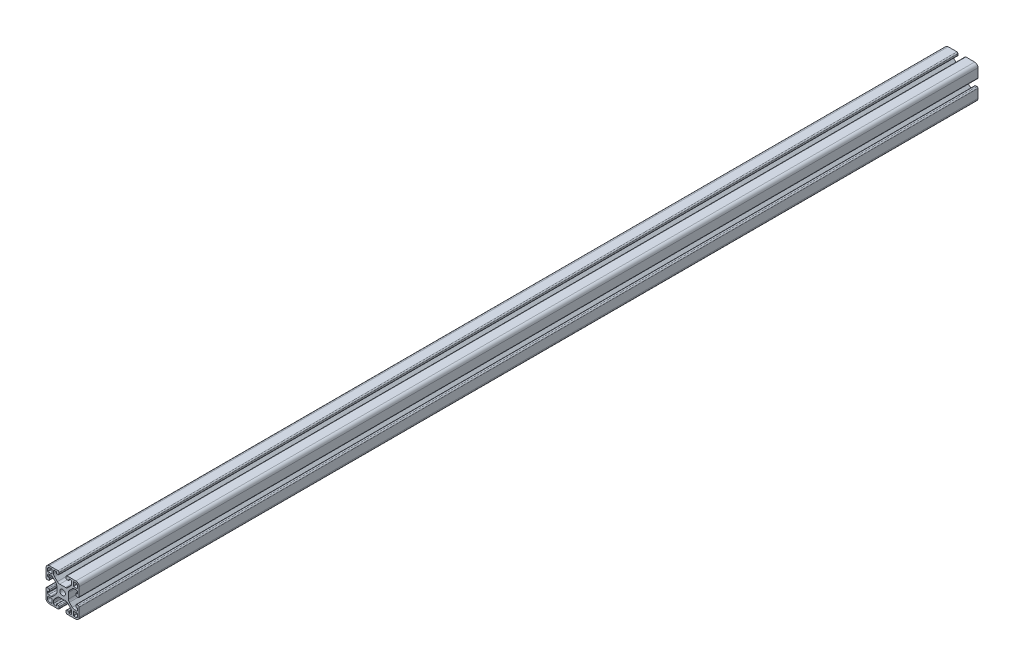
SolidWorks part; units mm, degrees
ref_plane "Plan de face" through (0, 0, 0) normal (0, 0, 1) x (1, 0, 0)
ref_plane "Plan de dessus" through (0, 0, 0) normal (0, 1, 0) x (1, 0, 0)
ref_plane "Plan de droite" through (0, 0, 0) normal (1, 0, 0) x (0, 0, -1)
ref_plane "Plan1" through (0, 0, 20) normal (0, 0, 1) x (1, 0, 0)
sketch "Esquisse1" plane through (0, 0, 20) normal (0, 0, 1) x (1, 0, 0)
  line L0 (20.3, 3) -> (18.9, 3)
  line L1 (18.1, 2.2) -> (18.1, 1)
  line L2 (19.1, 0) -> (27, 0)
  line L3 (30, 3) -> (30, 10.9)
  line L4 (29, 11.9) -> (27.8, 11.9)
  line L5 (27, 11.1) -> (27, 9.7)
  line L6 (27.3, 9.4) -> (28.2, 9.4)
  line L7 (28.5, 9.1) -> (28.5, 7.85)
  line L8 (27.5, 6.85) -> (25.8069, 6.85)
  line L9 (23.6855, 7.7287) -> (21.1287, 10.2855)
  line L10 (20.25, 12.4069) -> (20.25, 17.5931)
  line L11 (21.1287, 19.7145) -> (23.6855, 22.2713)
  line L12 (25.8069, 23.15) -> (27.5, 23.15)
  line L13 (28.5, 22.15) -> (28.5, 20.9)
  line L14 (28.2, 20.6) -> (27.3, 20.6)
  line L15 (27, 20.3) -> (27, 18.9)
  line L16 (27.8, 18.1) -> (29, 18.1)
  line L17 (30, 19.1) -> (30, 27)
  line L18 (27, 30) -> (19.1, 30)
  line L19 (18.1, 29) -> (18.1, 27.8)
  line L20 (18.9, 27) -> (20.3, 27)
  line L21 (20.6, 27.3) -> (20.6, 28.2)
  line L22 (20.9, 28.5) -> (22.15, 28.5)
  line L23 (23.15, 27.5) -> (23.15, 25.8069)
  line L24 (22.2713, 23.6855) -> (19.7145, 21.1287)
  line L25 (17.5931, 20.25) -> (12.4069, 20.25)
  line L26 (10.2855, 21.1287) -> (7.7287, 23.6855)
  line L27 (6.85, 25.8069) -> (6.85, 27.5)
  line L28 (7.85, 28.5) -> (9.1, 28.5)
  line L29 (9.4, 28.2) -> (9.4, 27.3)
  line L30 (9.7, 27) -> (11.1, 27)
  line L31 (11.9, 27.8) -> (11.9, 29)
  line L32 (10.9, 30) -> (3, 30)
  line L33 (0, 27) -> (0, 19.1)
  line L34 (1, 18.1) -> (2.2, 18.1)
  line L35 (3, 18.9) -> (3, 20.3)
  line L36 (2.7, 20.6) -> (1.8, 20.6)
  line L37 (1.5, 20.9) -> (1.5, 22.15)
  line L38 (2.5, 23.15) -> (4.1931, 23.15)
  line L39 (6.3145, 22.2713) -> (8.8713, 19.7145)
  line L40 (9.75, 17.5931) -> (9.75, 12.4069)
  line L41 (8.8713, 10.2855) -> (6.3145, 7.7287)
  line L42 (4.1931, 6.85) -> (2.5, 6.85)
  line L43 (1.5, 7.85) -> (1.5, 9.1)
  line L44 (1.8, 9.4) -> (2.7, 9.4)
  line L45 (3, 9.7) -> (3, 11.1)
  line L46 (2.2, 11.9) -> (1, 11.9)
  line L47 (0, 10.9) -> (0, 3)
  line L48 (3, 0) -> (10.9, 0)
  line L49 (11.9, 1) -> (11.9, 2.2)
  line L50 (11.1, 3) -> (9.7, 3)
  line L51 (9.4, 2.7) -> (9.4, 1.8)
  line L52 (9.1, 1.5) -> (7.85, 1.5)
  line L53 (6.85, 2.5) -> (6.85, 4.1931)
  line L54 (7.7287, 6.3145) -> (10.2855, 8.8713)
  line L55 (12.4069, 9.75) -> (17.5931, 9.75)
  line L56 (19.7145, 8.8713) -> (22.2713, 6.3145)
  line L57 (23.15, 4.1931) -> (23.15, 2.5)
  line L58 (22.15, 1.5) -> (20.9, 1.5)
  line L59 (20.6, 1.8) -> (20.6, 2.7)
  line L60 (5.35, 5.05) -> (5.35, 1.8)
  line L61 (5.05, 1.5) -> (3, 1.5)
  line L62 (1.5, 3) -> (1.5, 5.05)
  line L63 (1.8, 5.35) -> (5.05, 5.35)
  line L64 (24.95, 5.35) -> (28.2, 5.35)
  line L65 (28.5, 5.05) -> (28.5, 3)
  line L66 (27, 1.5) -> (24.95, 1.5)
  line L67 (24.65, 1.8) -> (24.65, 5.05)
  line L68 (24.65, 24.95) -> (24.65, 28.2)
  line L69 (24.95, 28.5) -> (27, 28.5)
  line L70 (28.5, 27) -> (28.5, 24.95)
  line L71 (28.2, 24.65) -> (24.95, 24.65)
  line L72 (5.05, 24.65) -> (1.8, 24.65)
  line L73 (1.5, 24.95) -> (1.5, 27)
  line L74 (3, 28.5) -> (5.05, 28.5)
  line L75 (5.35, 28.2) -> (5.35, 24.95)
  arc A0 (20.6, 2.7) -> (20.3, 3) centre (20.3, 2.7) ccw
  arc A1 (18.9, 3) -> (18.1, 2.2) centre (18.9, 2.2) ccw
  arc A2 (18.1, 1) -> (19.1, 0) centre (19.1, 1) ccw
  arc A3 (27, 0) -> (30, 3) centre (27, 3) ccw
  arc A4 (30, 10.9) -> (29, 11.9) centre (29, 10.9) ccw
  arc A5 (27.8, 11.9) -> (27, 11.1) centre (27.8, 11.1) ccw
  arc A6 (27, 9.7) -> (27.3, 9.4) centre (27.3, 9.7) ccw
  arc A7 (28.2, 9.4) -> (28.5, 9.1) centre (28.2, 9.1) cw
  arc A8 (28.5, 7.85) -> (27.5, 6.85) centre (27.5, 7.85) cw
  arc A9 (25.8069, 6.85) -> (23.6855, 7.7287) centre (25.8069, 9.85) cw
  arc A10 (21.1287, 10.2855) -> (20.25, 12.4069) centre (23.25, 12.4069) cw
  arc A11 (20.25, 17.5931) -> (21.1287, 19.7145) centre (23.25, 17.5931) cw
  arc A12 (23.6855, 22.2713) -> (25.8069, 23.15) centre (25.8069, 20.15) cw
  arc A13 (27.5, 23.15) -> (28.5, 22.15) centre (27.5, 22.15) cw
  arc A14 (28.5, 20.9) -> (28.2, 20.6) centre (28.2, 20.9) cw
  arc A15 (27.3, 20.6) -> (27, 20.3) centre (27.3, 20.3) ccw
  arc A16 (27, 18.9) -> (27.8, 18.1) centre (27.8, 18.9) ccw
  arc A17 (29, 18.1) -> (30, 19.1) centre (29, 19.1) ccw
  arc A18 (30, 27) -> (27, 30) centre (27, 27) ccw
  arc A19 (19.1, 30) -> (18.1, 29) centre (19.1, 29) ccw
  arc A20 (18.1, 27.8) -> (18.9, 27) centre (18.9, 27.8) ccw
  arc A21 (20.3, 27) -> (20.6, 27.3) centre (20.3, 27.3) ccw
  arc A22 (20.6, 28.2) -> (20.9, 28.5) centre (20.9, 28.2) cw
  arc A23 (22.15, 28.5) -> (23.15, 27.5) centre (22.15, 27.5) cw
  arc A24 (23.15, 25.8069) -> (22.2713, 23.6855) centre (20.15, 25.8069) cw
  arc A25 (19.7145, 21.1287) -> (17.5931, 20.25) centre (17.5931, 23.25) cw
  arc A26 (12.4069, 20.25) -> (10.2855, 21.1287) centre (12.4069, 23.25) cw
  arc A27 (7.7287, 23.6855) -> (6.85, 25.8069) centre (9.85, 25.8069) cw
  arc A28 (6.85, 27.5) -> (7.85, 28.5) centre (7.85, 27.5) cw
  arc A29 (9.1, 28.5) -> (9.4, 28.2) centre (9.1, 28.2) cw
  arc A30 (9.4, 27.3) -> (9.7, 27) centre (9.7, 27.3) ccw
  arc A31 (11.1, 27) -> (11.9, 27.8) centre (11.1, 27.8) ccw
  arc A32 (11.9, 29) -> (10.9, 30) centre (10.9, 29) ccw
  arc A33 (3, 30) -> (0, 27) centre (3, 27) ccw
  arc A34 (0, 19.1) -> (1, 18.1) centre (1, 19.1) ccw
  arc A35 (2.2, 18.1) -> (3, 18.9) centre (2.2, 18.9) ccw
  arc A36 (3, 20.3) -> (2.7, 20.6) centre (2.7, 20.3) ccw
  arc A37 (1.8, 20.6) -> (1.5, 20.9) centre (1.8, 20.9) cw
  arc A38 (1.5, 22.15) -> (2.5, 23.15) centre (2.5, 22.15) cw
  arc A39 (4.1931, 23.15) -> (6.3145, 22.2713) centre (4.1931, 20.15) cw
  arc A40 (8.8713, 19.7145) -> (9.75, 17.5931) centre (6.75, 17.5931) cw
  arc A41 (9.75, 12.4069) -> (8.8713, 10.2855) centre (6.75, 12.4069) cw
  arc A42 (6.3145, 7.7287) -> (4.1931, 6.85) centre (4.1931, 9.85) cw
  arc A43 (2.5, 6.85) -> (1.5, 7.85) centre (2.5, 7.85) cw
  arc A44 (1.5, 9.1) -> (1.8, 9.4) centre (1.8, 9.1) cw
  arc A45 (2.7, 9.4) -> (3, 9.7) centre (2.7, 9.7) ccw
  arc A46 (3, 11.1) -> (2.2, 11.9) centre (2.2, 11.1) ccw
  arc A47 (1, 11.9) -> (0, 10.9) centre (1, 10.9) ccw
  arc A48 (0, 3) -> (3, 0) centre (3, 3) ccw
  arc A49 (10.9, 0) -> (11.9, 1) centre (10.9, 1) ccw
  arc A50 (11.9, 2.2) -> (11.1, 3) centre (11.1, 2.2) ccw
  arc A51 (9.7, 3) -> (9.4, 2.7) centre (9.7, 2.7) ccw
  arc A52 (9.4, 1.8) -> (9.1, 1.5) centre (9.1, 1.8) cw
  arc A53 (7.85, 1.5) -> (6.85, 2.5) centre (7.85, 2.5) cw
  arc A54 (6.85, 4.1931) -> (7.7287, 6.3145) centre (9.85, 4.1931) cw
  arc A55 (10.2855, 8.8713) -> (12.4069, 9.75) centre (12.4069, 6.75) cw
  arc A56 (17.5931, 9.75) -> (19.7145, 8.8713) centre (17.5931, 6.75) cw
  arc A57 (22.2713, 6.3145) -> (23.15, 4.1931) centre (20.15, 4.1931) cw
  arc A58 (23.15, 2.5) -> (22.15, 1.5) centre (22.15, 2.5) cw
  arc A59 (20.9, 1.5) -> (20.6, 1.8) centre (20.9, 1.8) cw
  circle A60 centre (15, 15) radius 2.5
  arc A61 (5.05, 5.35) -> (5.35, 5.05) centre (5.05, 5.05) cw
  arc A62 (5.35, 1.8) -> (5.05, 1.5) centre (5.05, 1.8) cw
  arc A63 (3, 1.5) -> (1.5, 3) centre (3, 3) cw
  arc A64 (1.5, 5.05) -> (1.8, 5.35) centre (1.8, 5.05) cw
  arc A65 (24.65, 5.05) -> (24.95, 5.35) centre (24.95, 5.05) cw
  arc A66 (28.2, 5.35) -> (28.5, 5.05) centre (28.2, 5.05) cw
  arc A67 (28.5, 3) -> (27, 1.5) centre (27, 3) cw
  arc A68 (24.95, 1.5) -> (24.65, 1.8) centre (24.95, 1.8) cw
  arc A69 (24.95, 24.65) -> (24.65, 24.95) centre (24.95, 24.95) cw
  arc A70 (24.65, 28.2) -> (24.95, 28.5) centre (24.95, 28.2) cw
  arc A71 (27, 28.5) -> (28.5, 27) centre (27, 27) cw
  arc A72 (28.5, 24.95) -> (28.2, 24.65) centre (28.2, 24.95) cw
  arc A73 (5.35, 24.95) -> (5.05, 24.65) centre (5.05, 24.95) cw
  arc A74 (1.8, 24.65) -> (1.5, 24.95) centre (1.8, 24.95) cw
  arc A75 (1.5, 27) -> (3, 28.5) centre (3, 27) cw
  arc A76 (5.05, 28.5) -> (5.35, 28.2) centre (5.05, 28.2) cw
extrude "Boss.-Extru.1" add sketch "Esquisse1" against normal blind 813
